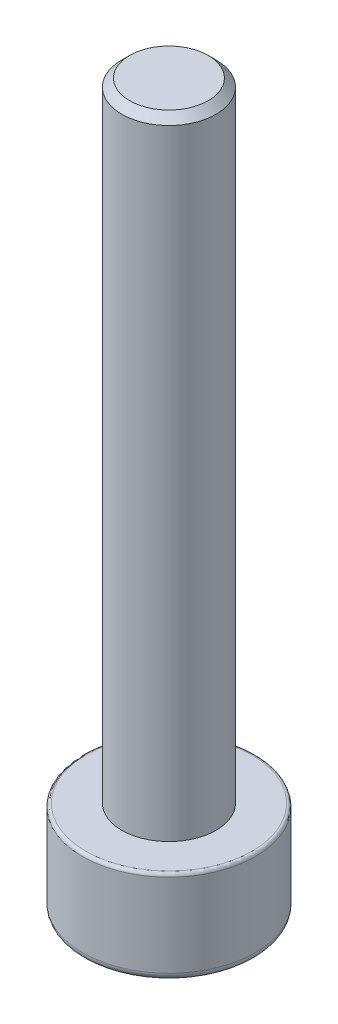
SolidWorks part; units mm, degrees
ref_plane "Front Plane" through (0, 0, 0) normal (0, 0, 1) x (1, 0, 0)
ref_plane "Top Plane" through (0, 0, 0) normal (0, 1, 0) x (1, 0, 0)
ref_plane "Right Plane" through (0, 0, 0) normal (1, 0, 0) x (0, 0, -1)
sketch "Sketch1" plane through (0, 0, 0) normal (0, 1, 0) x (1, 0, 0)
  circle A0 centre (0, 0) radius 2.75
  dimension "D1" = 5.5
extrude "Boss-Extrude1" add sketch "Sketch1" along normal blind 3
sketch "Sketch2" plane through (0, 3, 0) normal (0, 1, 0) x (1, 0, 0)
  circle A0 centre (0, 0) radius 1.5
  dimension "D1" = 3
extrude "Boss-Extrude2" add sketch "Sketch2" along normal blind 20 contours A0
sketch "Sketch3" plane through (0, 0, 0) normal (0, -1, 0) x (1, 0, 0)
  line L1 (0.9342, 0.9746) -> (-0.3769, 1.2963)
  line L2 (-0.3769, 1.2963) -> (-1.3111, 0.3217)
  line L3 (-1.3111, 0.3217) -> (-0.9342, -0.9746)
  line L4 (-0.9342, -0.9746) -> (0.3769, -1.2963)
  line L5 (0.3769, -1.2963) -> (1.3111, -0.3217)
  line L6 (1.3111, -0.3217) -> (0.9342, 0.9746)
  circle A0 centre (0, 0) radius 1.1691 construction
  dimension "D1" = 2.7
extrude "Cut-Extrude1" cut sketch "Sketch3" against normal blind 1.5
chamfer "Chamfer1" distance 0.25 distance2 0.25 6 edges at (-0.2786, 0, -1.1355) (-1.1226, 0, -0.3264) (-0.844, 0, 0.809) (0.2786, 0, 1.1355) (1.1226, 0, 0.3264) (0.844, 0, -0.809)
fillet "Fillet1" radius 0.25 1 edges at (0, 0, 2.75)
chamfer "Chamfer2" distance 0.25 angle 45 1 edges at (0, 23, 1.5)
fillet "Fillet2" radius 0.1 1 edges at (0, 3, 2.75)
